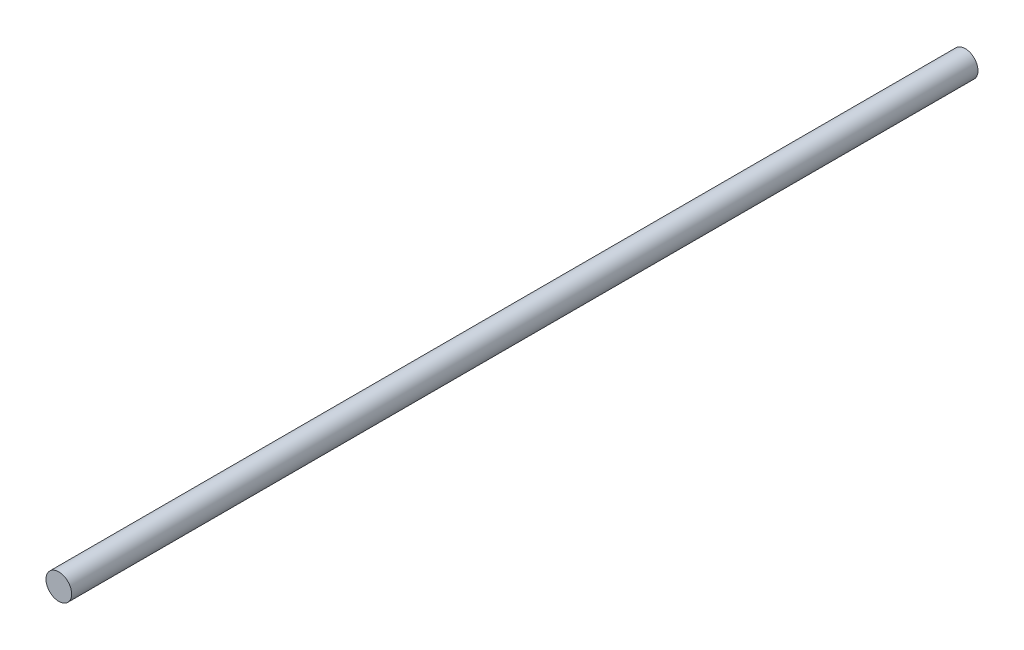
SolidWorks part; units mm, degrees
ref_plane "Plan de face" through (0, 0, 0) normal (0, 0, 1) x (1, 0, 0)
ref_plane "Plan de dessus" through (0, 0, 0) normal (0, 1, 0) x (1, 0, 0)
ref_plane "Plan de droite" through (0, 0, 0) normal (1, 0, 0) x (0, 0, -1)
sketch "Esquisse1" plane through (0, 0, 0) normal (0, 0, 1) x (1, 0, 0)
  circle A0 centre (0, 0) radius 2.39
  dimension "D1" = 4.78
extrude "Boss.-Extru.1" add sketch "Esquisse1" along normal blind 169
